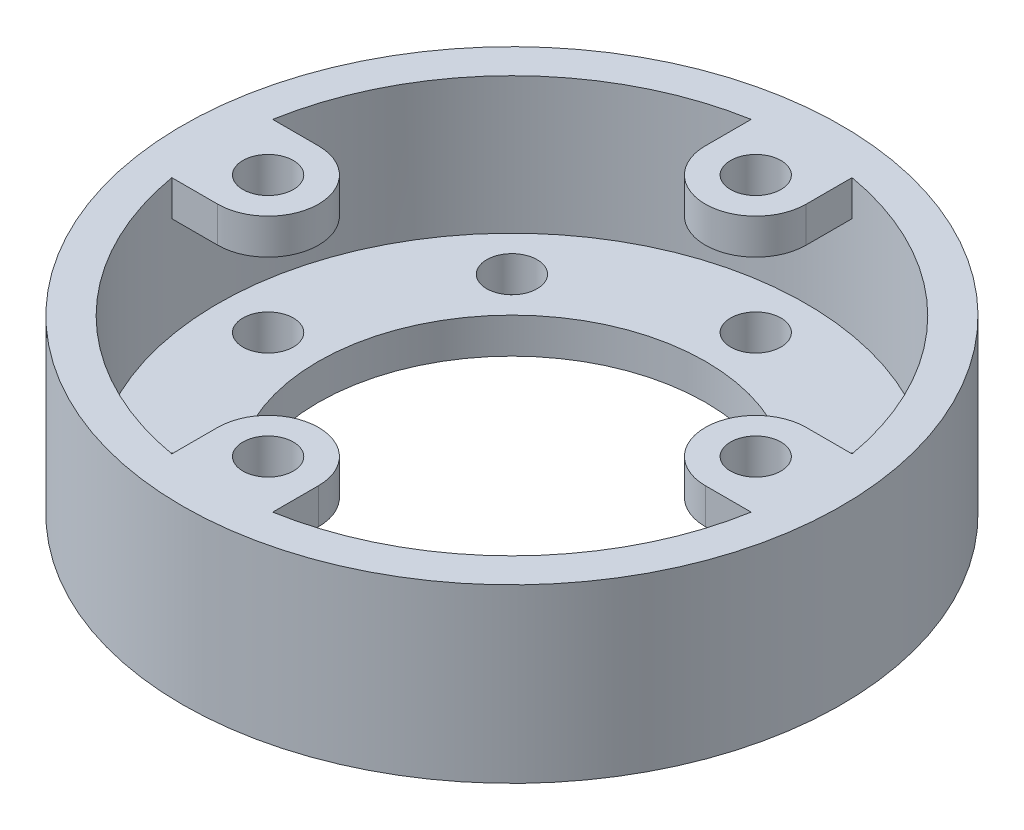
SolidWorks part; units mm, degrees
ref_plane "Front Plane" through (0, 0, 0) normal (0, 0, 1) x (1, 0, 0)
ref_plane "Top Plane" through (0, 0, 0) normal (0, 1, 0) x (1, 0, 0)
ref_plane "Right Plane" through (0, 0, 0) normal (1, 0, 0) x (0, 0, -1)
sketch "Sketch1" plane through (0, 0, 0) normal (0, 1, 0) x (1, 0, 0)
  circle A0 centre (0, 0) radius 73.025
  circle A1 centre (0, 0) radius 42.926
  dimension "D1" = 146.05
  dimension "D2" = 85.852
extrude "Boss-Extrude1" add sketch "Sketch1" along normal blind 7.874
sketch "Sketch2" plane through (0, 7.874, 0) normal (0, 1, 0) x (1, 0, 0)
  circle A1 centre (0, 0) radius 73.025 construction
  circle A2 centre (0, 0) radius 65.151
  circle A3 centre (0, 0) radius 65.151
  circle A4 centre (0, 0) radius 73.025
  dimension "D1" = 7.874
extrude "Boss-Extrude2" add sketch "Sketch2" along normal blind 30.226
sketch "Sketch3" plane through (0, 38.1, 0) normal (0, 1, 0) x (1, 0, 0)
  line L0 (-64.1853, 11.176) -> (-54.0253, 11.176)
  line L1 (-64.1853, -11.176) -> (-54.0253, -11.176)
  line L2 (-87.7792, 0) -> (83.6964, 0) construction
  line L3 (0, -88.1619) -> (0, 89.4378) construction
  line L4 (11.176, 64.1853) -> (11.176, 54.0253)
  line L5 (-11.176, 64.1853) -> (-11.176, 54.0253)
  line L6 (64.1853, -11.176) -> (54.0253, -11.176)
  line L7 (64.1853, 11.176) -> (54.0253, 11.176)
  line L8 (-11.176, -64.1853) -> (-11.176, -54.0253)
  line L9 (11.176, -64.1853) -> (11.176, -54.0253)
  circle A0 centre (0, 0) radius 65.151 construction
  arc A1 (-54.0253, 11.176) -> (-54.0253, -11.176) centre (-54.0253, 0) cw
  circle A2 centre (-54.0253, 0) radius 5.588
  arc A3 (11.176, 54.0253) -> (-11.176, 54.0253) centre (0, 54.0253) cw
  circle A4 centre (0, 54.0253) radius 5.588
  arc A5 (54.0253, -11.176) -> (54.0253, 11.176) centre (54.0253, 0) cw
  circle A6 centre (54.0253, 0) radius 5.588
  arc A7 (-11.176, -54.0253) -> (11.176, -54.0253) centre (0, -54.0253) cw
  circle A8 centre (0, -54.0253) radius 5.588
  point P13 (0, 0)
  point P14 (0, 0)
  circle M9 centre (0, 0) radius 65.151
  dimension "D2" = 11.176
  dimension "D3" = 11.176
  dimension "D1" = 10.16
  dimension "D4" = 4
extrude "Boss-Extrude3" add sketch "Sketch3" against normal blind 7.874 contours A1 L0 L1 A2 M9 | A3 L4 L5 A4 M9 | A5 L6 L7 A6 M9 | A7 L8 L9 A8 M9
sketch "Sketch4" plane through (0, 7.874, 0) normal (0, 1, 0) x (1, 0, 0)
  line L0 (-78.593, 0) -> (84.7171, 0) construction
  line L2 (0, 0) -> (-54.0253, 0) construction
  line L3 (0, 0) -> (-38.2016, 38.2016) construction
  circle A0 centre (-54.0253, 0) radius 5.588
  circle A1 centre (-54.0253, 0) radius 5.588 construction
  circle A2 centre (-38.2016, 38.2016) radius 5.588
  circle A3 centre (0, 54.0253) radius 5.588
  circle A4 centre (38.2016, 38.2016) radius 5.588
  circle A5 centre (54.0253, 0) radius 5.588
  circle A6 centre (38.2016, -38.2016) radius 5.588
  circle A7 centre (0, -54.0253) radius 5.588
  circle A8 centre (-38.2016, -38.2016) radius 5.588
  point P9 (-37.6233, 37.9569)
  point P10 (0, 0)
  dimension "D2" = 45
  dimension "D3" = 54.0253
  dimension "D1" = 8
extrude "Cut-Extrude1" cut sketch "Sketch4" against normal through all
